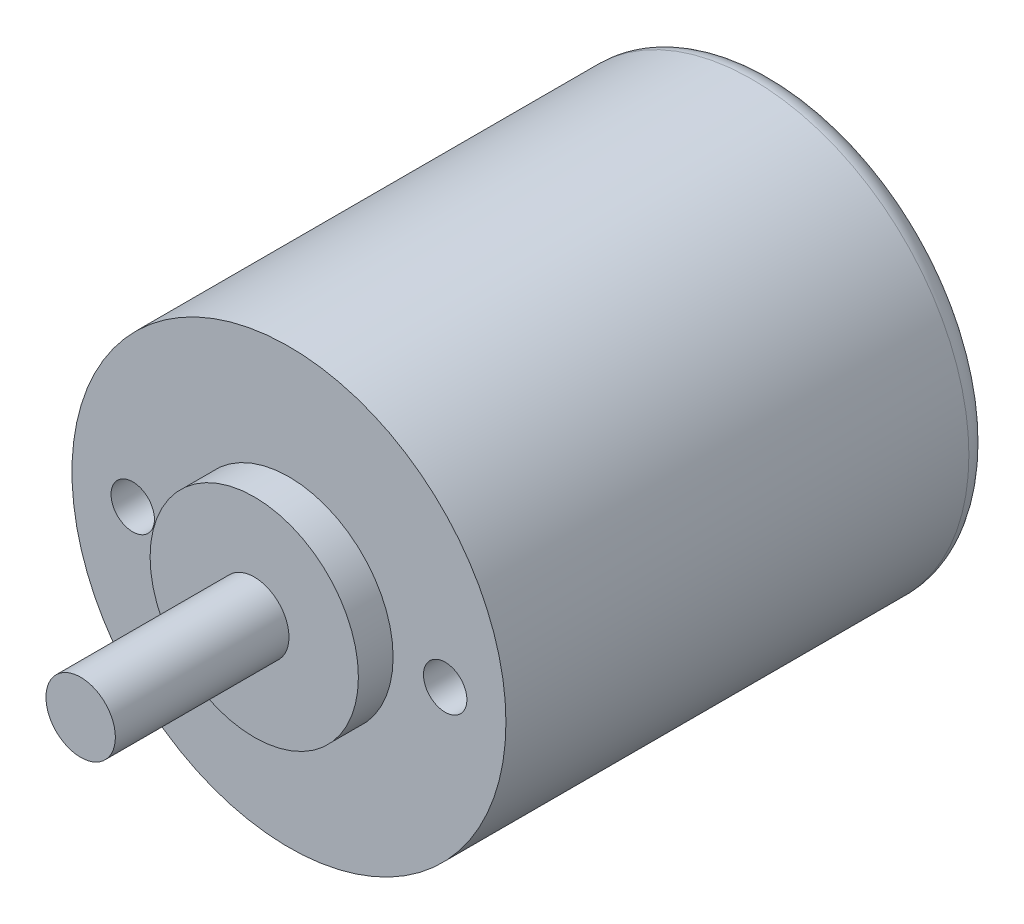
SolidWorks part; units mm, degrees
ref_plane "Front Plane" through (0, 0, 0) normal (0, 0, 1) x (1, 0, 0)
ref_plane "Top Plane" through (0, 0, 0) normal (0, 1, 0) x (1, 0, 0)
ref_plane "Right Plane" through (0, 0, 0) normal (1, 0, 0) x (0, 0, -1)
sketch "Sketch1" plane through (0, 0, 0) normal (0, 0, 1) x (1, 0, 0)
  circle A0 centre (0, 0) radius 12.5
  dimension "D1" = 25
extrude "Boss-Extrude1" add sketch "Sketch1" along normal blind 27.94
sketch "Sketch2" plane through (0, 0, 27.94) normal (0, 0, 1) x (1, 0, 0)
  circle A0 centre (0, 0) radius 6
  dimension "D1" = 12
extrude "Boss-Extrude2" add sketch "Sketch2" along normal blind 2
sketch "Sketch3" plane through (0, 0, 29.94) normal (0, 0, 1) x (1, 0, 0)
  circle A0 centre (0, 0) radius 2
  dimension "D1" = 4
extrude "Boss-Extrude3" add sketch "Sketch3" along normal blind 10
hole_wizard "M3x0.5 Tapped Hole1" positions "Sketch4" profile "Sketch5" tap size "M3x0.5" standard "ANSI Metric"
sketch "Sketch4" plane through (0, 0, 27.94) normal (0, 0, 1) x (1, 0, 0)
  line L0 (-9, 0) -> (9, 0) construction
  point P0 (-9, 0)
  point P2 (9, 0)
  dimension "D1" = 18
sketch "Sketch5" plane through (-9, 0, 27.94) normal (1, 0, 0) x (0, -1, 0)
  line L0 (0, 0) -> (0, 4.7511)
  line L1 (0, 4.7511) -> (1.25, 4)
  line L2 (1.25, 4) -> (1.25, 0)
  line L5 (1.25, 0) -> (0, 0)
  line L10 (0, 4.7511) -> (-1.25, 4) construction
  line L11 (0, -6.35) -> (0, 107.95) construction
  dimension "Tap Drill Dia." = 2.5
  dimension "Tap Drill Depth" = 4
  dimension "Drill Angle" = 118
cosmetic thread "Hole Thread1" parameters "D1"=4, "D2"=3
cosmetic thread "Hole Thread2" parameters "D1"=4, "D2"=3
fillet "Fillet1" radius 1.27 1 edges at (12.5, 0, 0)
